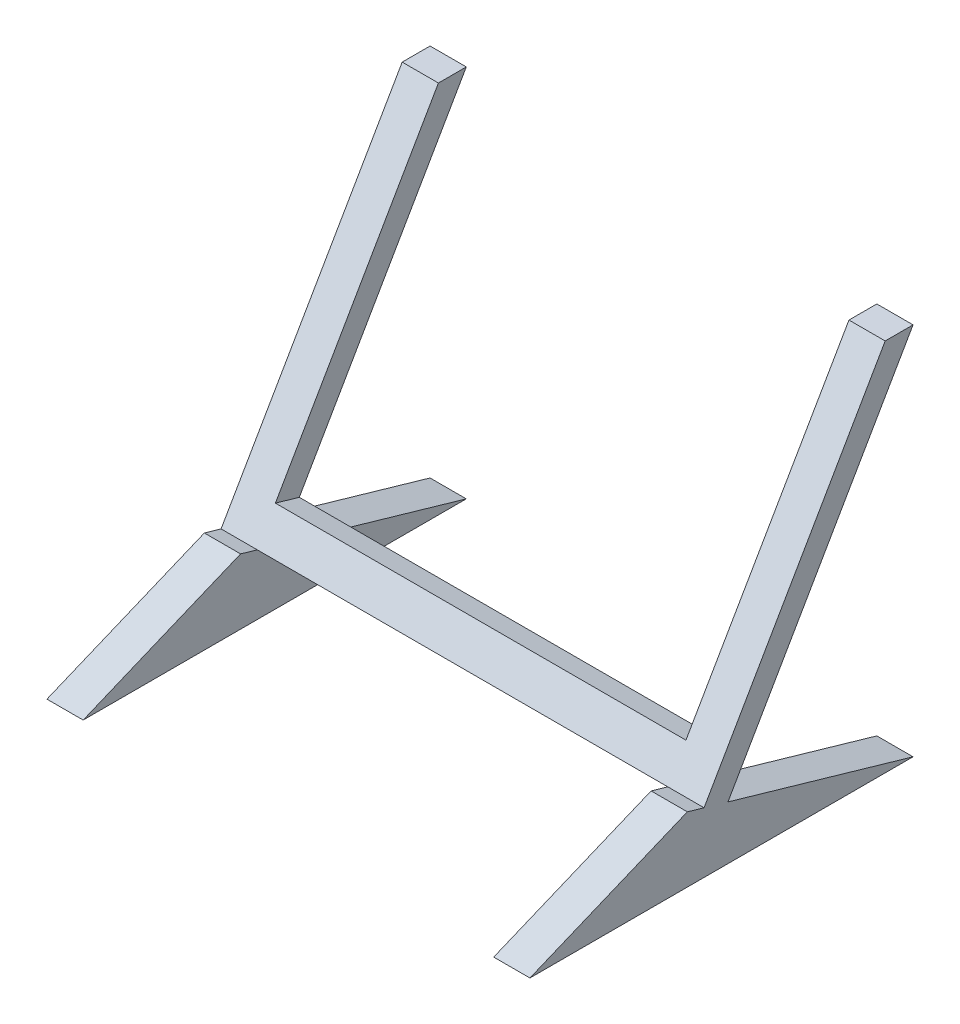
SolidWorks part; units mm, degrees
ref_plane "Front Plane" through (0, 0, 0) normal (0, 0, 1) x (1, 0, 0)
ref_plane "Top Plane" through (0, 0, 0) normal (0, 1, 0) x (1, 0, 0)
ref_plane "Right Plane" through (0, 0, 0) normal (1, 0, 0) x (0, 0, -1)
sketch "Sketch1" plane through (0, 0, 0) normal (1, 0, 0) x (0, 0, -1)
  line L0 (0, 0) -> (-12.8144, 0)
  line L1 (-12.8144, 0) -> (0.2214, 5.4)
  line L2 (0.2214, 5.4) -> (1.6061, 5)
  line L3 (1.6061, 5) -> (16.6061, 30.9808)
  line L4 (16.6061, 30.9808) -> (18.9155, 30.9808)
  line L5 (18.9155, 30.9808) -> (3.5854, 4.4283)
  line L6 (3.5854, 4.4283) -> (18.9155, 0)
  line L7 (18.9155, 0) -> (0, 0)
  point P3 (21.7347, 0)
  point P10 (-5.4359, 9.9726)
  point P11 (-5.4097, 10.0613)
  point P12 (-5.8726, 9.309)
  point P13 (7.5993, 0)
  point P14 (-15.533, 0)
  point P15 (11.0318, 0)
  point P16 (0, 0)
  point P17 (21.833, 0)
  point P18 (0, 0)
  point P19 (26.337, 0)
  point P20 (0, 0)
  point P21 (34.6809, 0)
  point P22 (19.9543, 0)
  point P23 (18.9155, 30.9808)
  point P24 (0, 0)
  dimension "D1" = 5
  dimension "D2" = 5.4
  dimension "D3" = 30
  dimension "D4" = 2
  dimension "D5" = 60
extrude "Boss-Extrude1" add sketch "Sketch1" along normal blind 3
ref_plane "Plane1" through (20, 0, 0) normal (1, 0, 0) x (0, 0, -1)
sketch "Sketch2" plane through (3, 0, 0) normal (1, 0, 0) x (0, 0, -1)
  line L0 (3.5854, 4.4283) -> (1.6061, 5)
  line L1 (3.5854, 4.4283) -> (5.0854, 7.0263)
  line L2 (1.6061, 5) -> (3.1061, 7.5981)
  line L3 (5.0854, 7.0263) -> (3.1061, 7.5981)
  line L4 (16.6061, 30.9808) -> (1.6061, 5) construction
  dimension "D1" = 3
sketch "Sketch3" plane through (20, 0, 0) normal (1, 0, 0) x (0, 0, -1)
  line L0 (3.5854, 4.4283) -> (18.9155, 30.9808) construction
  line L1 (16.6061, 30.9808) -> (1.6061, 5) construction
  line L2 (3.5854, 4.4283) -> (18.9155, 30.9808) construction
  line L3 (16.6061, 30.9808) -> (1.6061, 5) construction
  line L4 (3.5854, 4.4283) -> (1.6061, 5)
  line L5 (3.5854, 4.4283) -> (5.0854, 7.0263)
  line L6 (1.6061, 5) -> (3.1061, 7.5981)
  line L7 (5.0854, 7.0263) -> (3.1061, 7.5981)
  dimension "D1" = 3
extrude "Boss-Extrude3" add sketch "Sketch3" against normal up to surface (17 mm away) up to face at (3, 10.97, -6.7194)
mirror "Mirror5" about plane through (20, 0, 0) normal (1, 0, 0) of "Boss-Extrude3", "Boss-Extrude1"
mirror "Mirror6" about plane through (20, 0, 0) normal (1, 0, 0) of "Boss-Extrude1"
